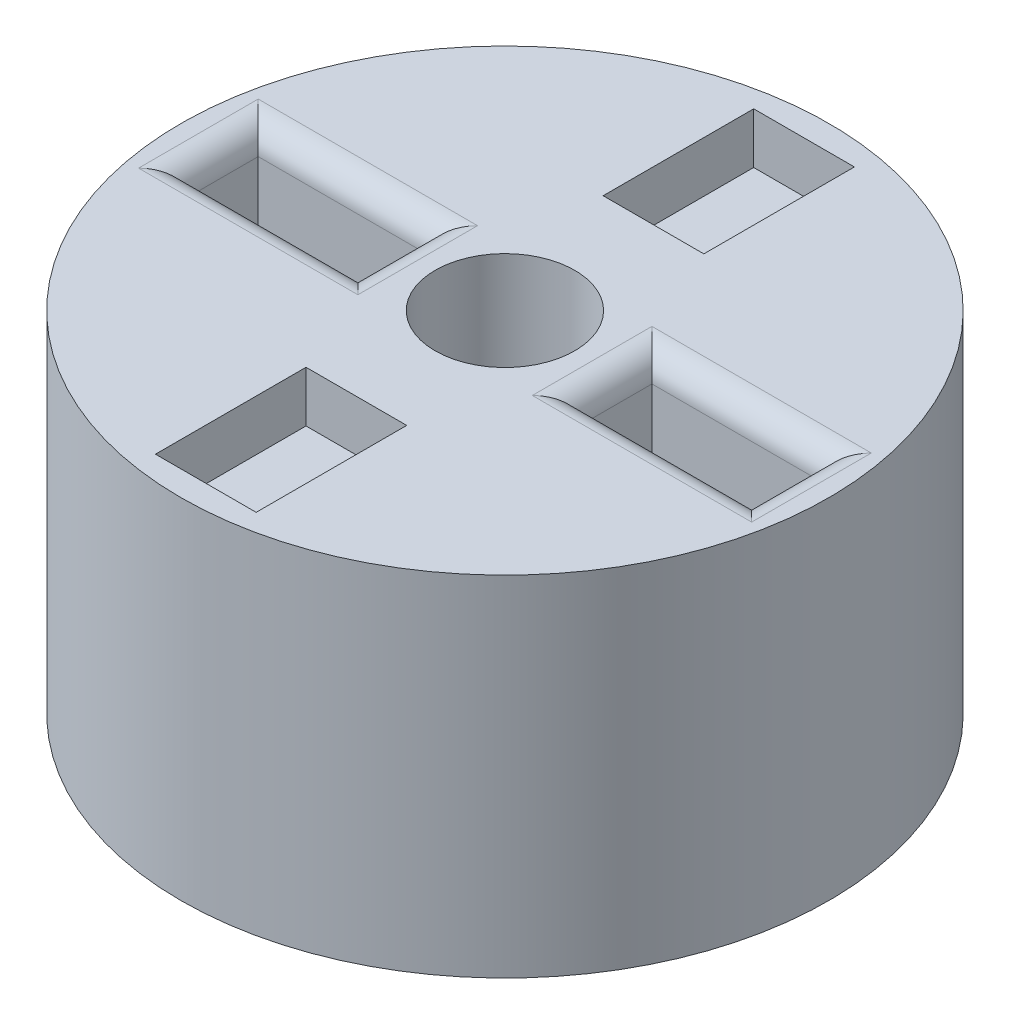
SolidWorks part; units mm, degrees
ref_plane "Front Plane" through (0, 0, 0) normal (0, 0, 1) x (1, 0, 0)
ref_plane "Top Plane" through (0, 0, 0) normal (0, 1, 0) x (1, 0, 0)
ref_plane "Right Plane" through (0, 0, 0) normal (1, 0, 0) x (0, 0, -1)
sketch "Sketch1" plane through (0, 0, 0) normal (0, 1, 0) x (1, 0, 0)
  circle A0 centre (0, 0) radius 32.5
  dimension "D1" = 65
extrude "Boss-Extrude1" add sketch "Sketch1" along normal blind 35 contours A0
sketch "Sketch2" plane through (0, 35, 0) normal (0, 1, 0) x (1, 0, 0)
  line L1 (-5.05, 30) -> (5.05, 30)
  line L2 (-5.05, 30) -> (-5.05, 14.9)
  line L3 (-5.05, 14.9) -> (5.05, 14.9)
  line L4 (5.05, 30) -> (5.05, 14.9)
  line L5 (5.05, -30) -> (5.05, -14.9)
  line L6 (-5.05, -14.9) -> (5.05, -14.9)
  line L7 (-5.05, -30) -> (-5.05, -14.9)
  line L8 (-5.05, -30) -> (5.05, -30)
  point P0 (0, 22.45)
  point P5 (0, -22.45)
  dimension "D3" = 0
extrude "Cut-Extrude1" cut sketch "Sketch2" against normal blind 5.1
sketch "Sketch3" plane through (0, 35, 0) normal (0, 1, 0) x (1, 0, 0)
  circle A0 centre (0, 0) radius 7
extrude "Cut-Extrude2" cut sketch "Sketch3" against normal through all
sketch "Sketch4" plane through (0, 35, 0) normal (0, 1, 0) x (1, 0, 0)
  line L0 (0, 0) -> (0, 11.6634) construction
  line L1 (11.2462, -3.5) -> (28.2462, -3.5)
  line L2 (11.2462, -3.5) -> (11.2462, 3.5)
  line L3 (11.2462, 3.5) -> (28.2462, 3.5)
  line L4 (28.2462, -3.5) -> (28.2462, 3.5)
  line L5 (-28.2462, -3.5) -> (-28.2462, 3.5)
  line L6 (-11.2462, 3.5) -> (-28.2462, 3.5)
  line L7 (-11.2462, -3.5) -> (-11.2462, 3.5)
  line L8 (-11.2462, -3.5) -> (-28.2462, -3.5)
  point P0 (19.7462, 0)
  point P9 (-19.7462, 0)
  dimension "D1" = 17
  dimension "D2" = 7
  dimension "D3" = 0
extrude "Cut-Extrude3" cut sketch "Sketch4" against normal blind 15
fillet "Fillet1" radius 2.5 8 edges at (28.2462, 35, 0) (19.7462, 35, 3.5) (11.2462, 35, 0) (19.7462, 35, -3.5) (-28.2462, 35, 0) (-19.7462, 35, 3.5) (-11.2462, 35, 0) (-19.7462, 35, -3.5)
